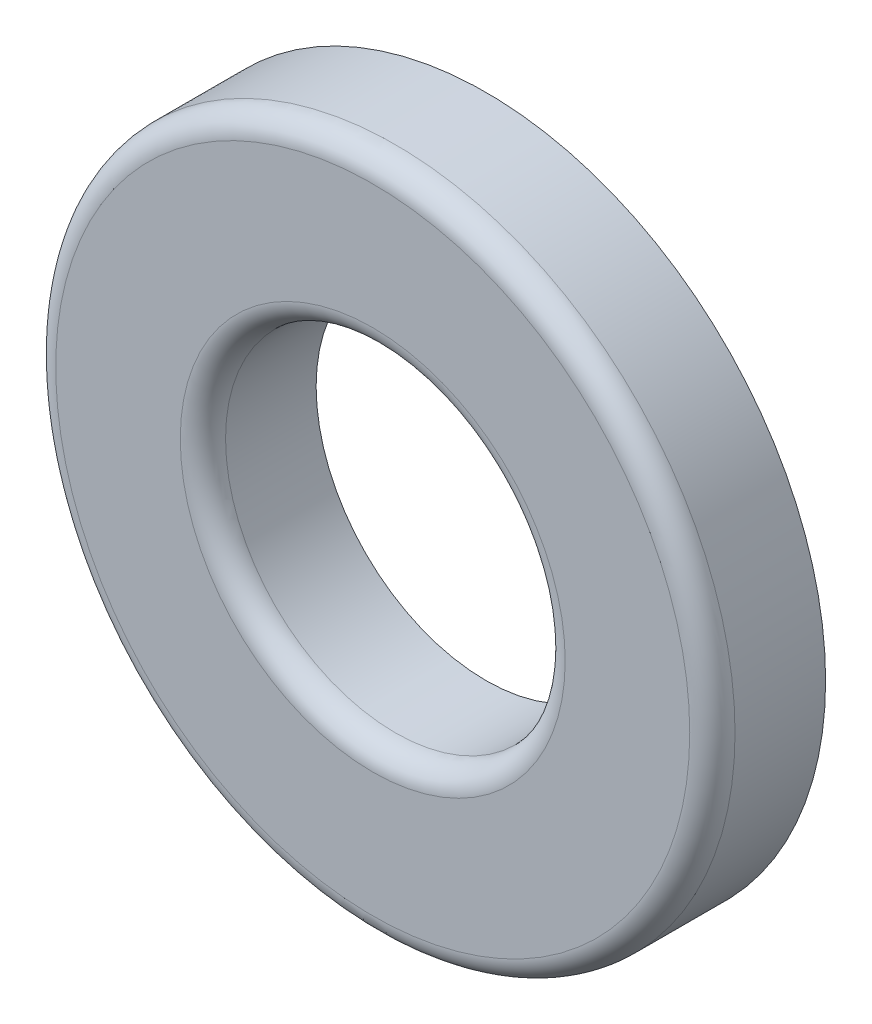
SolidWorks part; units mm, degrees
material "1.0037 (S235JR)"
ref_plane "Front Plane" through (0, 0, 0) normal (0, 0, 1) x (1, 0, 0)
ref_plane "Top Plane" through (0, 0, 0) normal (0, 1, 0) x (1, 0, 0)
ref_plane "Right Plane" through (0, 0, 0) normal (1, 0, 0) x (0, 0, -1)
sketch "Sketch1" plane through (0, 0, 0) normal (0, 0, 1) x (1, 0, 0)
  circle A0 centre (0, 0) radius 30
  circle A1 centre (0, 0) radius 15
  dimension "D1" = 60
  dimension "D2" = 30
extrude "Boss-Extrude1" add sketch "Sketch1" along normal blind 10
fillet "Fillet1" radius 2 2 edges at (15, 0, 10) (30, 0, 10)
